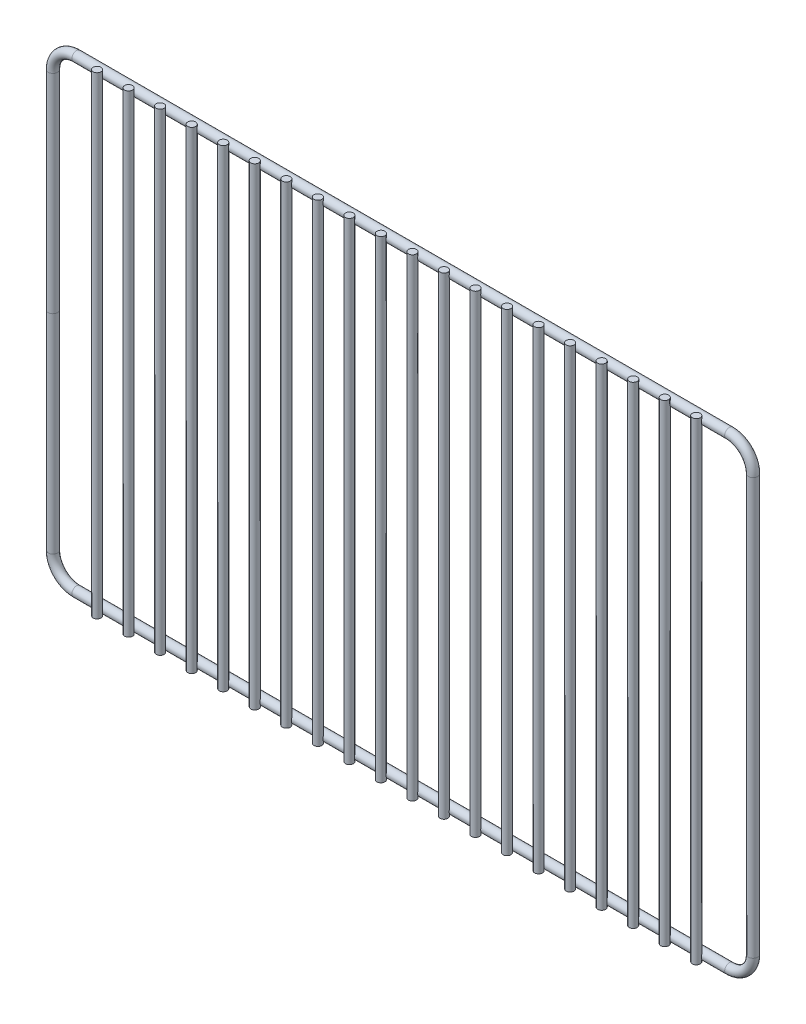
SolidWorks part; units mm, degrees
ref_plane "Front Plane" through (0, 0, 0) normal (0, 0, 1) x (1, 0, 0)
ref_plane "Top Plane" through (0, 0, 0) normal (0, 1, 0) x (1, 0, 0)
ref_plane "Right Plane" through (0, 0, 0) normal (1, 0, 0) x (0, 0, -1)
sketch "Sketch2" plane through (0, 0, 0) normal (0, 0, 1) x (1, 0, 0)
  line L0 (-222, 0) -> (222, 0) construction
  line L1 (207, 147) -> (-207, 147)
  line L2 (222, 132) -> (222, -132)
  line L3 (207, -147) -> (-207, -147)
  line L4 (-222, 132) -> (-222, -132)
  line L5 (222, 147) -> (-222, -147) construction
  line L6 (222, -147) -> (-222, 147) construction
  line L7 (-222, 147) -> (222, 147) construction
  arc A0 (207, 147) -> (222, 132) centre (207, 132) cw
  arc A1 (222, -132) -> (207, -147) centre (207, -132) cw
  arc A2 (-222, -132) -> (-207, -147) centre (-207, -132) ccw
  arc A3 (-222, 132) -> (-207, 147) centre (-207, 132) cw
  point P0 (0, 0)
  dimension "D3" = 15
  dimension "D1" = 444
  dimension "D2" = 294
sketch "Sketch3" plane through (0, 0, 0) normal (0, 1, 0) x (1, 0, 0)
  line L0 (222, 0) -> (-222, 0) construction
  circle A0 centre (-222, 0) radius 3
  dimension "D1" = 6
  dimension "D2" = 222
sweep "Sweep1" add profiles "Sketch3" path "Sketch2"
ref_plane "Plane1" through (0, 0, 4) normal (0, 0, 1) x (1, 0, 0)
sketch "Sketch4" plane through (0, 0, 4) normal (0, 0, 1) x (1, 0, 0)
  line L0 (-190, 150) -> (-190, -150)
  line L1 (207, 150) -> (-207, 150) construction
  line L2 (-207, -150) -> (207, -150) construction
  line L3 (-219, 0) -> (-219, 132) construction
  dimension "D1" = 29
sketch "Sketch5" plane through (0, 0, 0) normal (0, 1, 0) x (1, 0, 0)
  circle A1 centre (-190, -4) radius 2.5
  point P2 (-195.6402, -3.1545)
  point P4 (0, 0)
  dimension "D1" = 5
sweep "Sweep2" add profiles "Sketch5" path "Sketch4"
pattern_linear "LPattern1" count 20 spacing 20 along (1, 0, 0) of "Sweep2"
